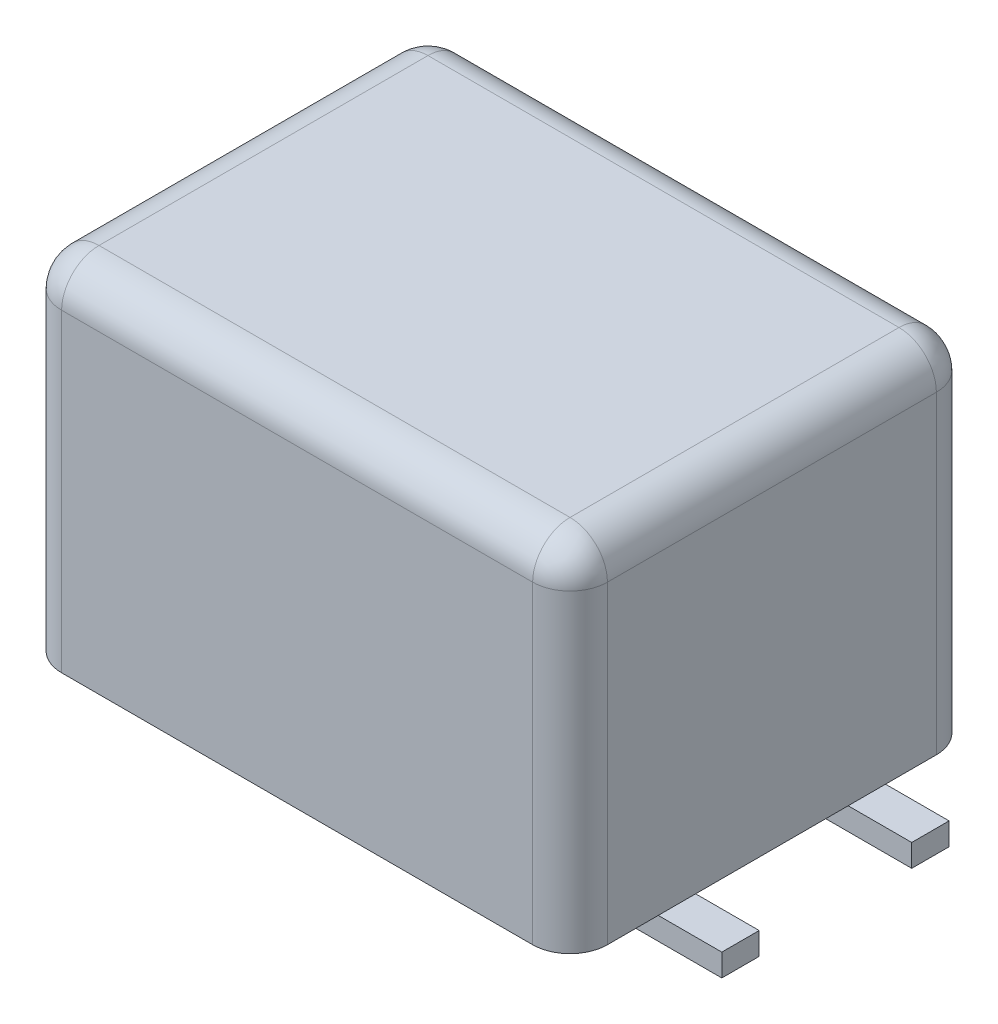
SolidWorks part; units mm, degrees
ref_plane "Front Plane" through (0, 0, 0) normal (0, 0, 1) x (1, 0, 0)
ref_plane "Top Plane" through (0, 0, 0) normal (0, 1, 0) x (1, 0, 0)
ref_plane "Right Plane" through (0, 0, 0) normal (1, 0, 0) x (0, 0, -1)
sketch "Sketch1" plane through (0, 0, 0) normal (0, 1, 0) x (1, 0, 0)
  line L1 (-3.15, 2.7) -> (3.15, 2.7)
  line L2 (-3.65, 2.2) -> (-3.65, -2.2)
  line L3 (-3.15, -2.7) -> (3.15, -2.7)
  line L4 (3.65, 2.2) -> (3.65, -2.2)
  line L5 (-3.65, 2.7) -> (3.65, -2.7) construction
  line L6 (-3.65, -2.7) -> (3.65, 2.7) construction
  arc A0 (3.15, -2.7) -> (3.65, -2.2) centre (3.15, -2.2) ccw
  arc A1 (-3.65, -2.2) -> (-3.15, -2.7) centre (-3.15, -2.2) ccw
  arc A2 (-3.15, 2.7) -> (-3.65, 2.2) centre (-3.15, 2.2) ccw
  arc A3 (3.15, 2.7) -> (3.65, 2.2) centre (3.15, 2.2) cw
  point P0 (0, 0)
  dimension "D3" = 0.5
  dimension "D1" = 5.4
  dimension "D2" = 7.3
extrude "Boss-Extrude1" add sketch "Sketch1" along normal blind 4.7 from offset 0.3
sketch "Sketch2" plane through (0, 0, 0) normal (0, 1, 0) x (1, 0, 0)
  line L0 (3.625, 1.27) -> (3.625, -1.27) construction
  line L1 (2.75, -1.02) -> (4.5, -1.02)
  line L2 (2.75, -1.02) -> (2.75, -1.52)
  line L3 (2.75, -1.52) -> (4.5, -1.52)
  line L4 (4.5, -1.02) -> (4.5, -1.52)
  line L5 (2.75, -1.02) -> (4.5, -1.52) construction
  line L6 (2.75, -1.52) -> (4.5, -1.02) construction
  line L7 (2.75, 1.52) -> (4.5, 1.52)
  line L8 (2.75, 1.52) -> (2.75, 1.02)
  line L9 (2.75, 1.02) -> (4.5, 1.02)
  line L10 (4.5, 1.52) -> (4.5, 1.02)
  line L11 (2.75, 1.52) -> (4.5, 1.02) construction
  line L12 (2.75, 1.02) -> (4.5, 1.52) construction
  line L13 (0, 2.8564) -> (0, -3.0685) construction
  line L14 (-2.75, 1.02) -> (-4.5, 1.52) construction
  line L15 (-2.75, 1.52) -> (-4.5, 1.02) construction
  line L16 (-2.75, -1.52) -> (-4.5, -1.02) construction
  line L17 (-2.75, -1.02) -> (-4.5, -1.52) construction
  line L18 (-3.625, 1.27) -> (-3.625, -1.27) construction
  line L19 (-4.5, 1.52) -> (-4.5, 1.02)
  line L20 (-2.75, 1.02) -> (-4.5, 1.02)
  line L21 (-2.75, 1.52) -> (-2.75, 1.02)
  line L22 (-2.75, 1.52) -> (-4.5, 1.52)
  line L23 (-4.5, -1.02) -> (-4.5, -1.52)
  line L24 (-2.75, -1.52) -> (-4.5, -1.52)
  line L25 (-2.75, -1.02) -> (-2.75, -1.52)
  line L26 (-2.75, -1.02) -> (-4.5, -1.02)
  point P0 (3.625, -1.27)
  point P5 (3.625, 1.27)
  point P12 (3.625, 0)
  point P26 (-3.625, 0)
  dimension "D1" = 0.5
  dimension "D2" = 1.75
  dimension "D3" = 2.54
  dimension "D4" = 9
extrude "Boss-Extrude2" add sketch "Sketch2" along normal up to surface (0.3 mm away) up to face at (0, 0.3, 0)
fillet "Fillet1" radius 0.5 8 edges at (-3.5036, 5, 2.5536) (-3.65, 5, 0) (-3.5036, 5, -2.5536) (0, 5, -2.7) (3.5036, 5, -2.5536) (3.65, 5, 0) (3.5036, 5, 2.5536) (0, 5, 2.7)
